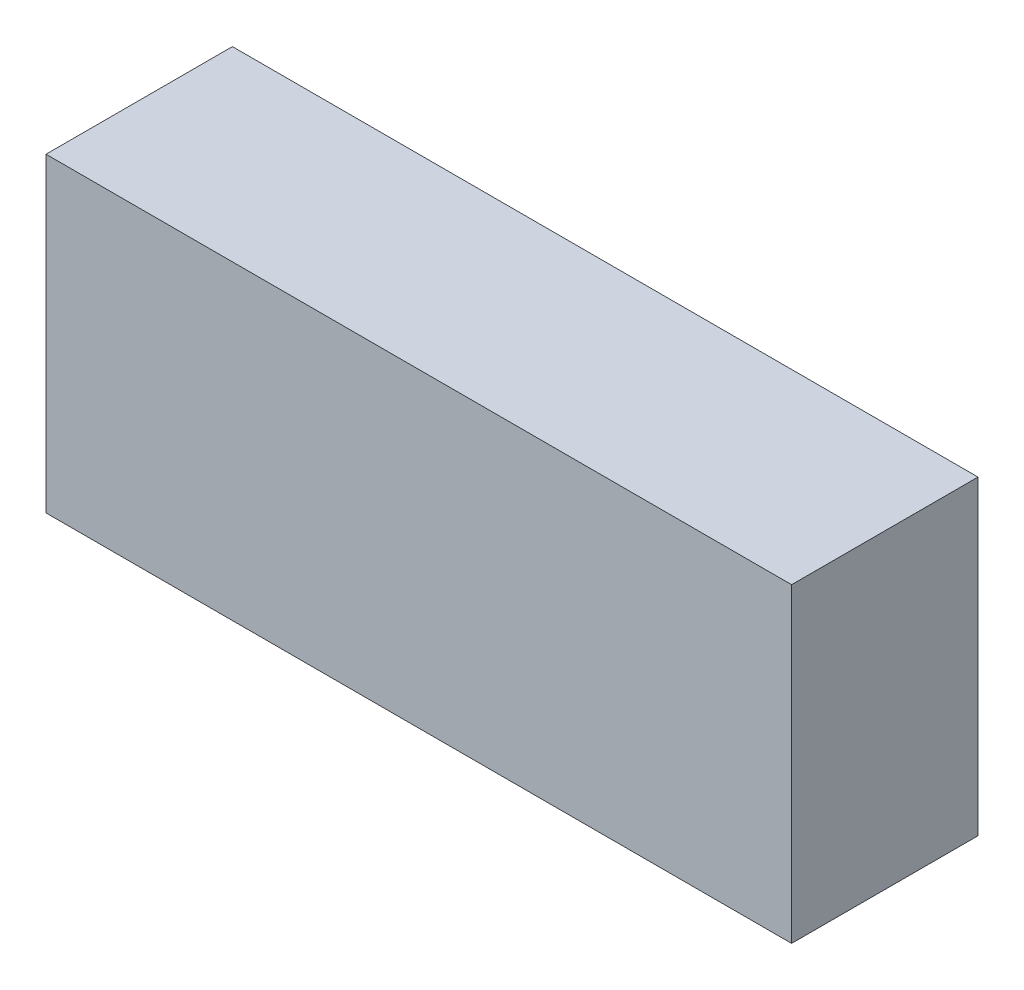
SolidWorks part; units mm, degrees
ref_plane "Front Plane" through (0, 0, 0) normal (0, 0, 1) x (1, 0, 0)
ref_plane "Top Plane" through (0, 0, 0) normal (0, 1, 0) x (1, 0, 0)
ref_plane "Right Plane" through (0, 0, 0) normal (1, 0, 0) x (0, 0, -1)
sketch "Sketch1" plane through (0, 0, 0) normal (1, 0, 0) x (0, 0, -1)
  line L1 (0, 0) -> (3, 0)
  line L2 (0, 0) -> (0, 5)
  line L3 (0, 5) -> (3, 5)
  line L4 (3, 0) -> (3, 5)
  dimension "D1" = 5
  dimension "D2" = 3
extrude "Boss-Extrude1" add sketch "Sketch1" along normal blind 12
